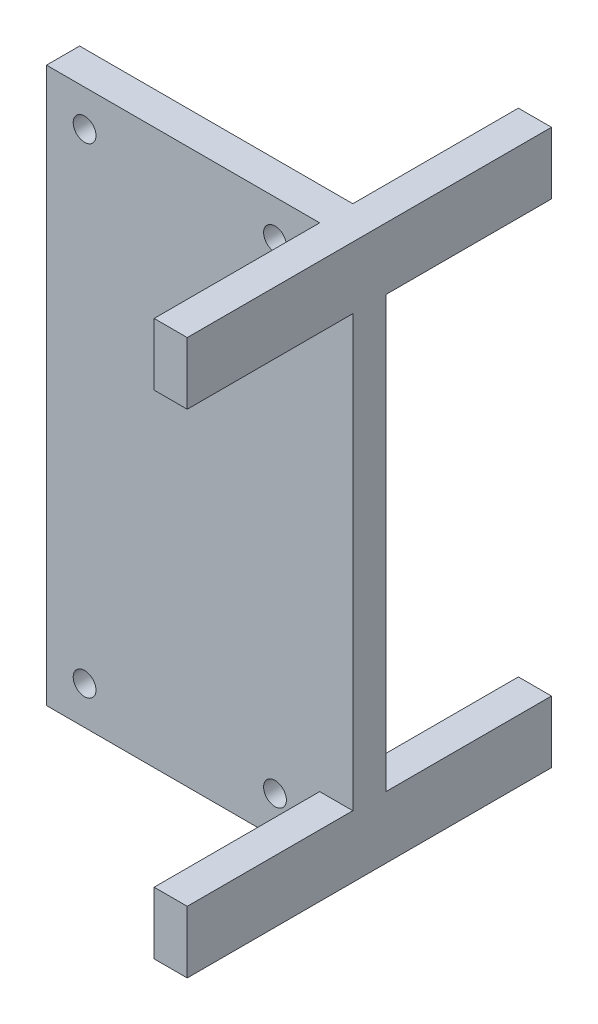
SolidWorks part; units mm, degrees
ref_plane "Płaszczyzna przednia" through (0, 0, 0) normal (0, 0, 1) x (1, 0, 0)
ref_plane "Płaszczyzna górna" through (0, 0, 0) normal (0, 1, 0) x (1, 0, 0)
ref_plane "Płaszczyzna prawa" through (0, 0, 0) normal (1, 0, 0) x (0, 0, -1)
sketch "Szkic2" plane through (0, 0, 0) normal (0, 0, 1) x (1, 0, 0)
  line L1 (0, 0) -> (32, 0)
  line L2 (0, 0) -> (0, 67)
  line L3 (0, 67) -> (32, 67)
  line L4 (32, 0) -> (32, 67)
  line L5 (32, 0) -> (37, 0)
  line L6 (32, 0) -> (32, 67)
  line L7 (32, 67) -> (37, 67)
  line L8 (37, 0) -> (37, 67)
  circle A0 centre (4.6, 62.6) radius 1.375
  circle A1 centre (27.6, 62.6) radius 1.375
  circle A2 centre (4.6, 4.6) radius 1.375
  circle A3 centre (27.6, 4.6) radius 1.375
  point P27 (0, 0)
  point P28 (0, 0)
  point P29 (0, 0)
  point P30 (0, 0)
  dimension "D1" = 32
  dimension "D4" = 2.75
  dimension "D5" = 2.75
  dimension "D6" = 2.75
  dimension "D7" = 2.75
  dimension "D12" = 4.4
  dimension "D2" = 67
  dimension "D3" = 5
  dimension "D8" = 4.6
  dimension "D9" = 23
  dimension "D10" = 23
  dimension "D11" = 58
extrude "Dodanie-wyciągnięcie1" add sketch "Szkic2" along normal blind 4 contours L2 L1 L4 L3 | L6 L5 L8 L7 | A0 | A1 | A2 | A3
sketch "Szkic7" plane through (37, 0, 0) normal (1, 0, 0) x (0, 0, -1)
  line L0 (-4, 0) -> (-24, 0)
  line L1 (-24, 0) -> (-24, 7.5)
  line L2 (-24, 7.5) -> (-4, 7.5)
  line L3 (-4, 0) -> (-4, 67) construction
  line L4 (-2, 0) -> (-2, 67) construction
  line L5 (-4, 0) -> (0, 0) construction
  line L6 (-4, 67) -> (0, 67) construction
  line L7 (-4, 33.5) -> (0, 33.5) construction
  line L8 (0, 0) -> (0, 67) construction
  line L9 (-4, 7.5) -> (-4, 0)
  line L10 (20, 7.5) -> (0, 7.5)
  line L11 (20, 0) -> (20, 7.5)
  line L12 (0, 0) -> (20, 0)
  line L13 (0, 7.5) -> (0, 0)
  line L14 (-24, 59.5) -> (-4, 59.5)
  line L15 (-24, 67) -> (-24, 59.5)
  line L16 (-4, 67) -> (-24, 67)
  line L17 (-4, 59.5) -> (-4, 67)
  line L18 (20, 67) -> (20, 59.5)
  line L19 (0, 67) -> (20, 67)
  line L20 (0, 59.5) -> (0, 67)
  line L21 (20, 59.5) -> (0, 59.5)
  dimension "D1" = 20
  dimension "D2" = 7.5
extrude "Dodanie-wyciągnięcie2" add sketch "Szkic7" against normal blind 4 contours L14 L17 L16 L15 | L18 L21 L20 L19 | L10 L13 L12 L11 | L9 L0 L1 L2
